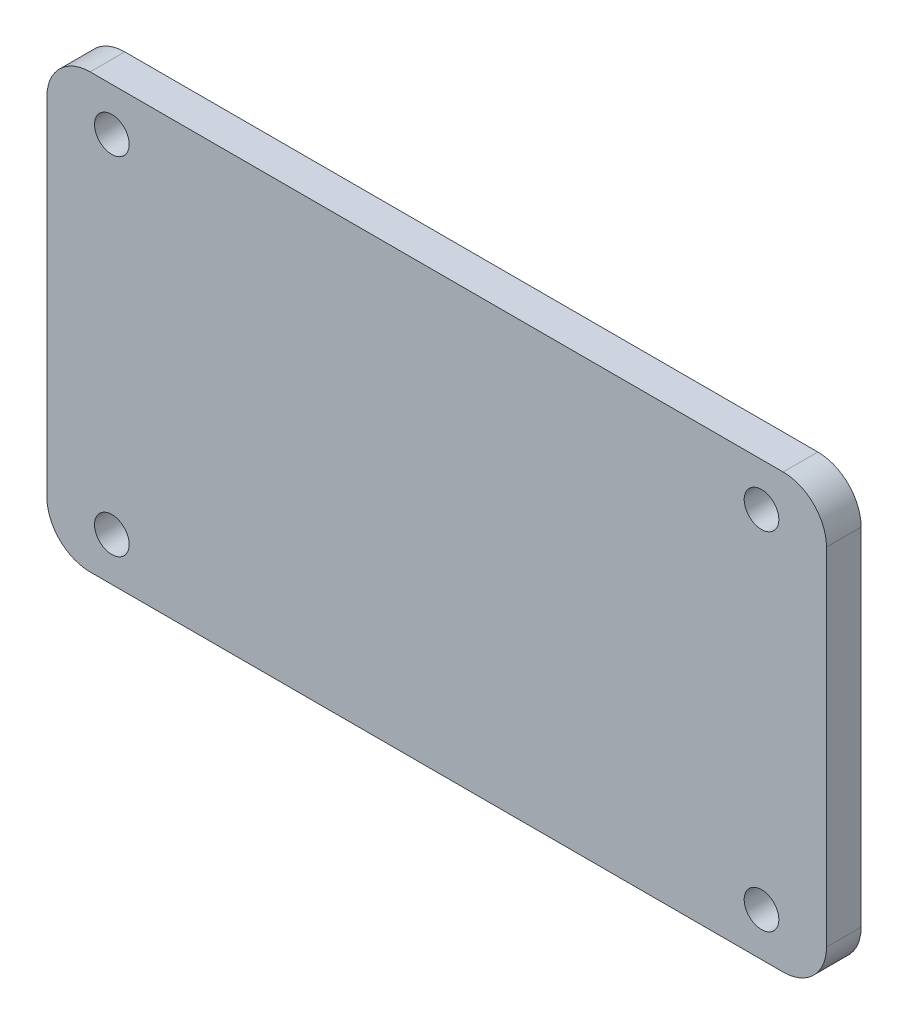
SolidWorks part; units mm, degrees
ref_plane "前视基准面" through (0, 0, 0) normal (0, 0, 1) x (1, 0, 0)
ref_plane "上视基准面" through (0, 0, 0) normal (0, 1, 0) x (1, 0, 0)
ref_plane "右视基准面" through (0, 0, 0) normal (1, 0, 0) x (0, 0, -1)
other "Configuration Table"
sketch "草图1" plane through (0, 0, 0) normal (0, 0, 1) x (1, 0, 0)
  line L1 (-45, -25) -> (45, -25)
  line L2 (-45, -25) -> (-45, 25)
  line L3 (-45, 25) -> (45, 25)
  line L4 (45, -25) -> (45, 25)
  line L5 (-45, -25) -> (45, 25) construction
  line L6 (-45, 25) -> (45, -25) construction
  line L7 (-37.5, -20) -> (37.5, -20) construction
  line L8 (-37.5, -20) -> (-37.5, 20) construction
  line L9 (-37.5, 20) -> (37.5, 20) construction
  line L10 (37.5, -20) -> (37.5, 20) construction
  line L11 (-37.5, -20) -> (37.5, 20) construction
  line L12 (-37.5, 20) -> (37.5, -20) construction
  circle A0 centre (-37.5, 20) radius 2
  circle A1 centre (-37.5, -20) radius 2
  circle A2 centre (37.5, -20) radius 2
  circle A3 centre (37.5, 20) radius 2
  point P0 (0, 0)
  point P6 (0, 0)
  dimension "D5" = 4
  dimension "D1" = 50
  dimension "D2" = 90
  dimension "D3" = 75
  dimension "D4" = 40
extrude "凸台-拉伸1" add sketch "草图1" along normal blind 4
fillet "圆角1" radius 5 4 edges at (-45, -25, 2) (45, -25, 2) (45, 25, 2) (-45, 25, 2)
